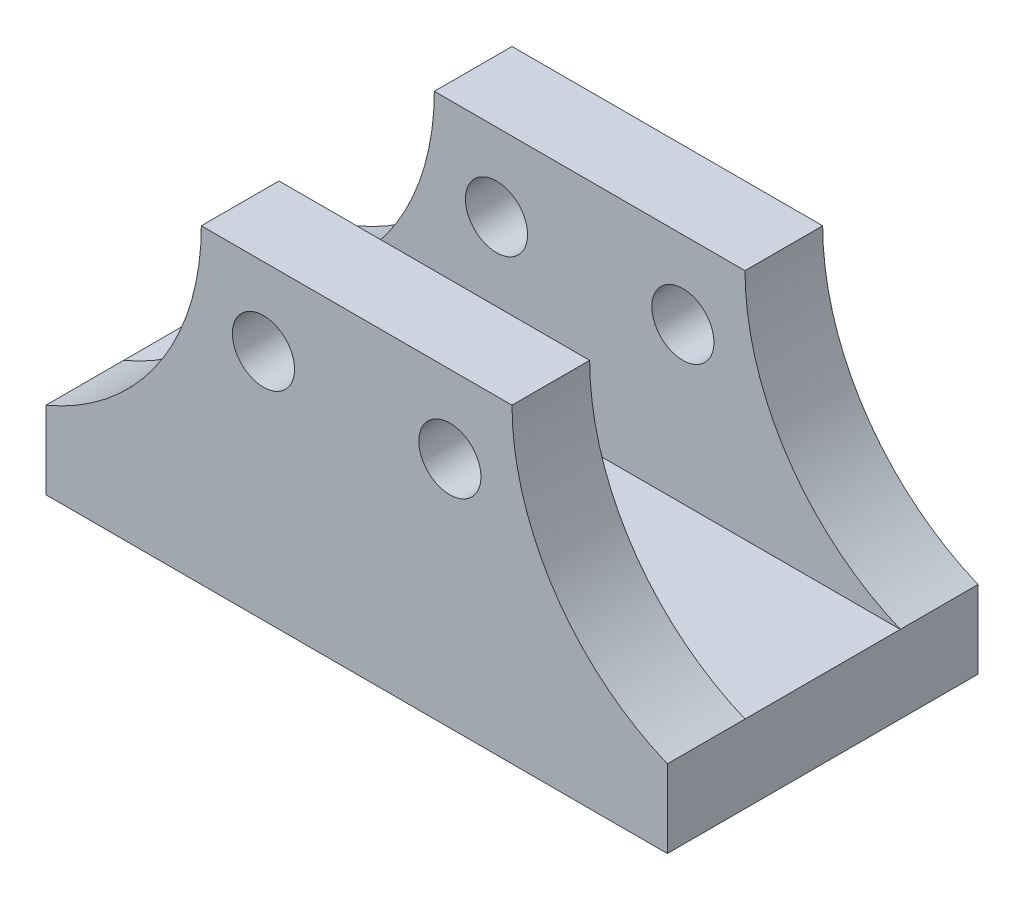
SolidWorks part; units mm, degrees
ref_plane "Front Plane" through (0, 0, 0) normal (0, 0, 1) x (1, 0, 0)
ref_plane "Top Plane" through (0, 0, 0) normal (0, 1, 0) x (1, 0, 0)
ref_plane "Right Plane" through (0, 0, 0) normal (1, 0, 0) x (0, 0, -1)
sketch "Sketch1" plane through (0, 0, 0) normal (0, 1, 0) x (1, 0, 0)
  line L1 (-200, 100) -> (200, 100)
  line L2 (-200, 100) -> (-200, -100)
  line L3 (-200, -100) -> (200, -100)
  line L4 (200, 100) -> (200, -100)
  dimension "D1" = 200
  dimension "D2" = 400
  dimension "D3" = 200
  dimension "D4" = 100
extrude "Boss-Extrude1" add sketch "Sketch1" along normal blind 50
sketch "Sketch2" plane through (0, 0, 0) normal (0, 0, 1) x (1, 0, 0)
  line L0 (-200, 50) -> (200, 50) construction
  line L1 (-100, 50) -> (100, 50)
  line L3 (-100, 200) -> (100, 200)
  line L5 (0, 337.9965) -> (0, -72.8237) construction
  line L6 (-200, 50) -> (-100, 50)
  line L7 (200, 50) -> (100, 50)
  arc A0 (-200, 50) -> (-100, 200) centre (-262.5, 200) ccw
  arc A1 (200, 50) -> (100, 200) centre (262.5, 200) cw
  dimension "D3" = 150
extrude "Boss-Extrude2" add sketch "Sketch2" along normal blind 100 and the other way blind 100
sketch "Sketch3" plane through (0, 0, 0) normal (1, 0, 0) x (0, 0, -1)
  line L0 (-100, 50) -> (100, 50) construction
  line L1 (-50, 235.844) -> (50, 235.844)
  line L2 (-50, 235.844) -> (-50, 50)
  line L3 (-50, 50) -> (50, 50)
  line L4 (50, 235.844) -> (50, 50)
  dimension "D1" = 100
  dimension "D2" = 50
extrude "Cut-Extrude1" cut sketch "Sketch3" against normal blind 200 and the other way blind 200
sketch "Sketch4" plane through (0, 0, 0) normal (0, 0, 1) x (1, 0, 0)
  line L0 (-200, 0) -> (200, 0) construction
  circle A0 centre (-60, 150) radius 20
  circle A1 centre (60, 150) radius 20
  dimension "D1" = 40
  dimension "D2" = 40
  dimension "D3" = 60
  dimension "D4" = 60
  dimension "D5" = 150
  dimension "D6" = 150
extrude "Cut-Extrude2" cut sketch "Sketch4" against normal blind 200 and the other way blind 200
